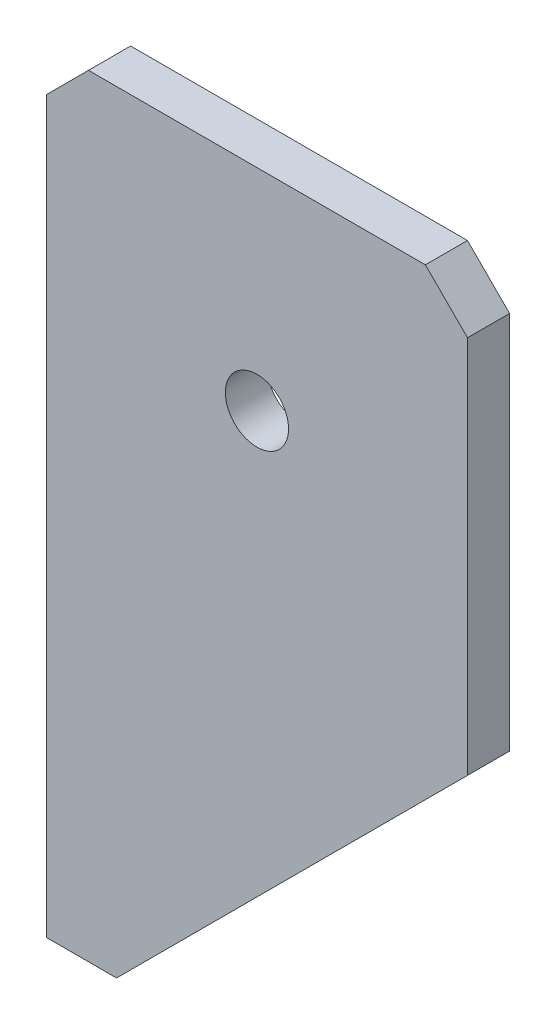
SolidWorks part; units mm, degrees
ref_plane "Front Plane" through (0, 0, 0) normal (0, 0, 1) x (1, 0, 0)
ref_plane "Top Plane" through (0, 0, 0) normal (0, 1, 0) x (1, 0, 0)
ref_plane "Right Plane" through (0, 0, 0) normal (1, 0, 0) x (0, 0, -1)
sketch "Sketch1" plane through (0, 0, 0) normal (0, 0, 1) x (1, 0, 0)
  line L1 (-15, -27.5) -> (15, -27.5)
  line L2 (-15, -27.5) -> (-15, 27.5)
  line L3 (-15, 27.5) -> (15, 27.5)
  line L4 (15, -27.5) -> (15, 27.5)
  line L5 (-15, -27.5) -> (15, 27.5) construction
  line L6 (-15, 27.5) -> (15, -27.5) construction
  point P0 (0, 0)
  dimension "D1" = 55
  dimension "D2" = 30
extrude "Boss-Extrude1" add sketch "Sketch1" along normal mid plane 3
chamfer "Chamfer1" distance 3 angle 45 2 edges at (-15, 27.5, 0) (15, 27.5, 0)
sketch "Sketch2" plane through (0, 0, 1.5) normal (0, 0, 1) x (1, 0, 0)
  line L0 (-15, 24.5) -> (-15, -27.5) construction
  line L1 (15, 27.5) -> (-15, 27.5) construction
  line L2 (15, 27.5) -> (15, -2.5) construction
  line L3 (15, -2.5) -> (-15, -2.5) construction
  line L4 (-15, 27.5) -> (-15, -2.5) construction
  line L5 (15, 27.5) -> (-15, -2.5) construction
  line L6 (15, -2.5) -> (-15, 27.5) construction
  line L7 (12, 27.5) -> (-12, 27.5) construction
  line L8 (15, -27.5) -> (15, 24.5) construction
  circle A0 centre (0, 12.5) radius 2.25
  point P0 (0, 12.5)
  dimension "D1" = 4.5
extrude "Cut-Extrude1" cut sketch "Sketch2" against normal blind 10 contours A0
chamfer "Chamfer2" distance 25 distance2 25 1 edges at (15, -27.5, 0)
